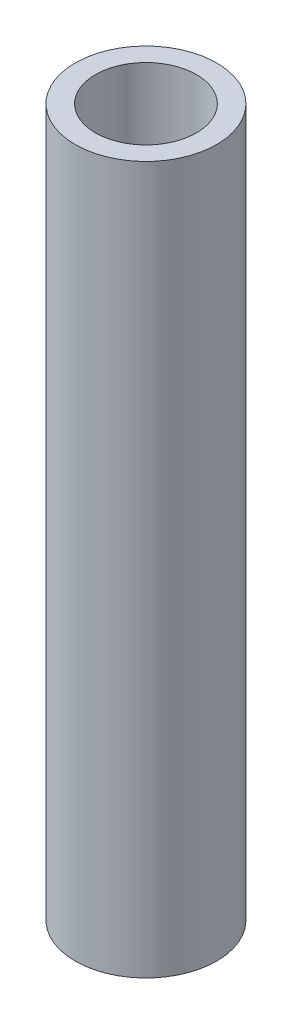
SolidWorks part; units mm, degrees
ref_plane "前视基准面" through (0, 0, 0) normal (0, 0, 1) x (1, 0, 0)
ref_plane "上视基准面" through (0, 0, 0) normal (0, 1, 0) x (1, 0, 0)
ref_plane "右视基准面" through (0, 0, 0) normal (1, 0, 0) x (0, 0, -1)
sketch "草图1" plane through (0, 0, 0) normal (0, 1, 0) x (1, 0, 0)
  circle A0 centre (0, 0) radius 3.5
  circle A1 centre (0, 0) radius 2.5
  dimension "D1" = 5
  dimension "D2" = 7
extrude "凸台-拉伸1" add sketch "草图1" along normal blind 35
